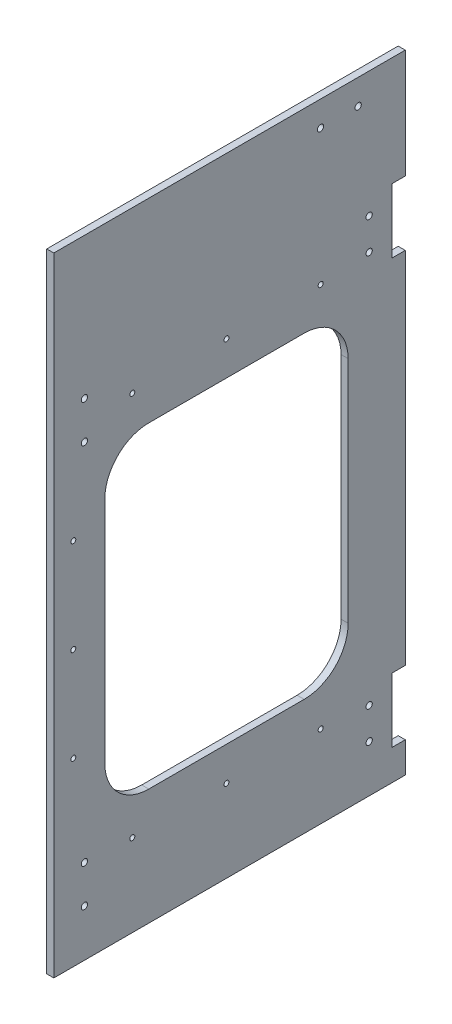
SolidWorks part; units mm, degrees
material "ABS PC"
ref_plane "前视基准面" through (0, 0, 0) normal (0, 0, 1) x (1, 0, 0)
ref_plane "上视基准面" through (0, 0, 0) normal (0, 1, 0) x (1, 0, 0)
ref_plane "右视基准面" through (0, 0, 0) normal (1, 0, 0) x (0, 0, -1)
sketch "草图1" plane through (0, 0, 0) normal (1, 0, 0) x (0, 0, -1)
  line L1 (0, 0) -> (-223.9, 0)
  line L2 (0, 0) -> (0, 400)
  line L3 (0, 400) -> (-223.9, 400)
  line L4 (-223.9, 0) -> (-223.9, 400)
  dimension "D1" = 223.9
  dimension "D2" = 400
extrude "凸台-拉伸1" add sketch "草图1" along normal blind 4.5
sketch "草图2" plane through (4.5, 0, 0) normal (1, 0, 0) x (0, 0, -1)
  line L0 (-204.4, 30) -> (-204.4, 54) construction
  line L1 (-204.4, 286) -> (-204.4, 310) construction
  line L2 (-223.9, 400) -> (-223.9, 0) construction
  line L3 (-223.9, 0) -> (0, 0) construction
  line L4 (0, 400) -> (-223.9, 400) construction
  line L5 (-54, 384) -> (-30, 384) construction
  line L6 (0, 0) -> (0, 400) construction
  line L7 (-23, 0) -> (-23, 319.3572) construction
  line L9 (0, 330.5) -> (-8.5, 330.5)
  line L10 (0, 330.5) -> (0, 289.5)
  line L11 (0, 289.5) -> (-8.5, 289.5)
  line L12 (-8.5, 330.5) -> (-8.5, 289.5)
  line L13 (0, 19.5) -> (-8.5, 19.5)
  line L14 (0, 19.5) -> (0, 60.5)
  line L15 (0, 60.5) -> (-8.5, 60.5)
  line L16 (-8.5, 19.5) -> (-8.5, 60.5)
  circle A0 centre (-204.4, 310) radius 2
  circle A1 centre (-204.4, 286) radius 2
  circle A2 centre (-204.4, 54) radius 2
  circle A3 centre (-204.4, 30) radius 2
  circle A4 centre (-54, 384) radius 2
  circle A5 centre (-30, 384) radius 2
  circle A6 centre (-23, 320) radius 2
  circle A7 centre (-23, 300) radius 2
  circle A8 centre (-23, 50) radius 2
  circle A9 centre (-23, 30) radius 2
  dimension "D3" = 4
  dimension "D9" = 4
  dimension "D10" = 4
  dimension "D1" = 24
  dimension "D2" = 24
  dimension "D4" = 19.5
  dimension "D5" = 30
  dimension "D6" = 90
  dimension "D7" = 19.5
  dimension "D8" = 24
  dimension "D11" = 16
  dimension "D12" = 30
  dimension "D13" = 20
  dimension "D14" = 20
  dimension "D15" = 30
  dimension "D16" = 300
  dimension "D17" = 23
  dimension "D18" = 8.5
  dimension "D19" = 41
  dimension "D20" = 19.5
  dimension "D21" = 8.5
  dimension "D22" = 41
  dimension "D23" = 289.5
extrude "切除-拉伸1" cut sketch "草图2" against normal blind 10
sketch "草图3" plane through (4.5, 0, 0) normal (1, 0, 0) x (0, 0, -1)
  line L0 (-223.9, 0) -> (0, 0) construction
  line L1 (-64.4, 74) -> (-163.4, 74)
  line L2 (-36.4, 102) -> (-36.4, 248)
  line L3 (-64.4, 276) -> (-163.4, 276)
  line L4 (-191.4, 102) -> (-191.4, 248)
  line L5 (-36.4, 74) -> (-191.4, 276) construction
  line L6 (-36.4, 276) -> (-191.4, 74) construction
  line L7 (-113.9, 175) -> (-211.5, 175) construction
  line L8 (-223.9, 400) -> (-223.9, 0) construction
  line L9 (-211.5, 175) -> (-211.5, 297.6) construction
  line L10 (-113.9, 175) -> (-113.9, 297.6) construction
  line L11 (-113.9, 297.6) -> (-211.5, 297.6) construction
  arc A0 (-163.4, 74) -> (-191.4, 102) centre (-163.4, 102) cw
  arc A1 (-64.4, 74) -> (-36.4, 102) centre (-64.4, 102) ccw
  arc A2 (-36.4, 248) -> (-64.4, 276) centre (-64.4, 248) ccw
  arc A3 (-163.4, 276) -> (-191.4, 248) centre (-163.4, 248) ccw
  circle A4 centre (-211.5, 175) radius 1.6
  circle A5 centre (-211.5, 235) radius 1.6
  circle A6 centre (-211.5, 115) radius 1.6
  circle A7 centre (-173.9, 297.6) radius 1.6
  circle A8 centre (-53.9, 297.6) radius 1.6
  circle A9 centre (-53.9, 52.4) radius 1.6
  circle A10 centre (-173.9, 52.4) radius 1.6
  circle A11 centre (-113.9, 297.6) radius 1.6
  circle A12 centre (-113.9, 52.4) radius 1.6
  point P0 (-113.9, 175)
  dimension "D5" = 28
  dimension "D7" = 3.2
  dimension "D11" = 3.2
  dimension "D1" = 155
  dimension "D2" = 202
  dimension "D3" = 175
  dimension "D4" = 110
  dimension "D6" = 60
  dimension "D8" = 60
  dimension "D9" = 97.6
  dimension "D10" = 122.6
extrude "切除-拉伸2" cut sketch "草图3" against normal up to next
